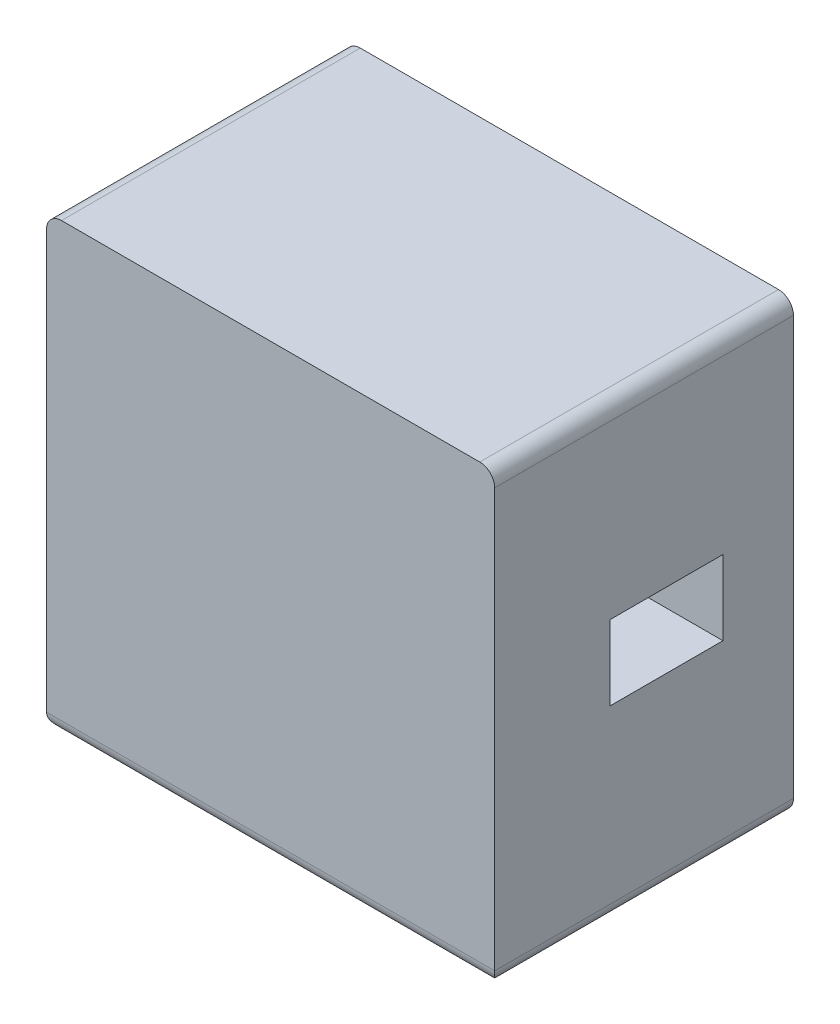
SolidWorks part; units mm, degrees
ref_plane "前视基准面" through (0, 0, 0) normal (0, 0, 1) x (1, 0, 0)
ref_plane "上视基准面" through (0, 0, 0) normal (0, 1, 0) x (1, 0, 0)
ref_plane "右视基准面" through (0, 0, 0) normal (1, 0, 0) x (0, 0, -1)
sketch "草图1" plane through (0, 0, 0) normal (0, 0, 1) x (1, 0, 0)
  line L0 (0, 150) -> (0, -79.1436) construction
  line L1 (-150, -150) -> (150, -150)
  line L2 (-150, -150) -> (-150, 150)
  line L3 (-150, 150) -> (150, 150)
  line L4 (150, -150) -> (150, 150)
  line L5 (-150, 0) -> (101.3492, 0) construction
  point P0 (0, 0)
  dimension "D1" = 300
extrude "凸台-拉伸3" add sketch "草图1" along normal blind 200
sketch "草图5" plane through (0, 0, 0) normal (0, 0, -1) x (-1, 0, 0)
  circle A0 centre (0, 0) radius 32.35
  dimension "D1" = 64.7
extrude "切除-拉伸3" cut sketch "草图5" against normal blind 62
sketch "草图6" plane through (0, 0, 0) normal (0, 0, -1) x (-1, 0, 0)
  circle A0 centre (0, 0) radius 38.24
  dimension "D1" = 76.48
extrude "切除-拉伸4" cut sketch "草图6" against normal blind 23.7
sketch "草图8" plane through (-150, 0, 0) normal (-1, 0, 0) x (0, 0, 1)
  line L0 (0, 0) -> (122.8122, 0) construction
  line L1 (47.21, -25) -> (47.21, 25)
  line L2 (47.21, 25) -> (122.8122, 25)
  line L3 (122.8122, 25) -> (122.8122, -25)
  line L4 (122.8122, -25) -> (47.21, -25)
  line L5 (0, 150) -> (0, -150) construction
  dimension "D1" = 47.21
  dimension "D2" = 50
extrude "切除-拉伸5" cut sketch "草图8" against normal up to next
sketch "草图10" plane through (0, 0, 23.7) normal (0, 0, -1) x (-1, 0, 0)
  line L0 (0, -32.35) -> (0, -38.24) construction
  line L1 (0, -32.35) -> (105.4624, -32.35) construction
  line L2 (0, -35.295) -> (-48.2394, -35.295) construction
  circle A2 centre (0, 0) radius 38.24 construction
  circle A3 centre (0, 0) radius 38.24 construction
  arc A4 (-20.531, -25) -> (20.531, -25) centre (0, 0) ccw construction
  circle A5 centre (0, -35.295) radius 1.35
  circle A6 centre (-14.3558, -32.2436) radius 1.35
  circle A7 centre (-26.2293, -23.617) radius 1.35
  circle A8 centre (-33.5675, -10.9068) radius 1.35
  circle A9 centre (-35.1017, 3.6893) radius 1.35
  circle A10 centre (-30.5664, 17.6475) radius 1.35
  circle A11 centre (-20.7459, 28.5543) radius 1.35
  circle A12 centre (-7.3382, 34.5237) radius 1.35
  circle A13 centre (7.3382, 34.5237) radius 1.35
  circle A14 centre (20.7459, 28.5543) radius 1.35
  circle A15 centre (30.5664, 17.6475) radius 1.35
  circle A16 centre (35.1017, 3.6893) radius 1.35
  circle A17 centre (33.5675, -10.9068) radius 1.35
  circle A18 centre (26.2293, -23.617) radius 1.35
  circle A19 centre (14.3558, -32.2436) radius 1.35
  point P46 (0, 0)
  dimension "D1" = 2.7
  dimension "D2" = 15
extrude "切除-拉伸7" cut sketch "草图10" against normal blind 5
fillet "圆角1" radius 10 5 edges at (0, -150, 200) (150, -150, 100) (-150, -150, 100) (-150, 150, 100) (150, 150, 100)
